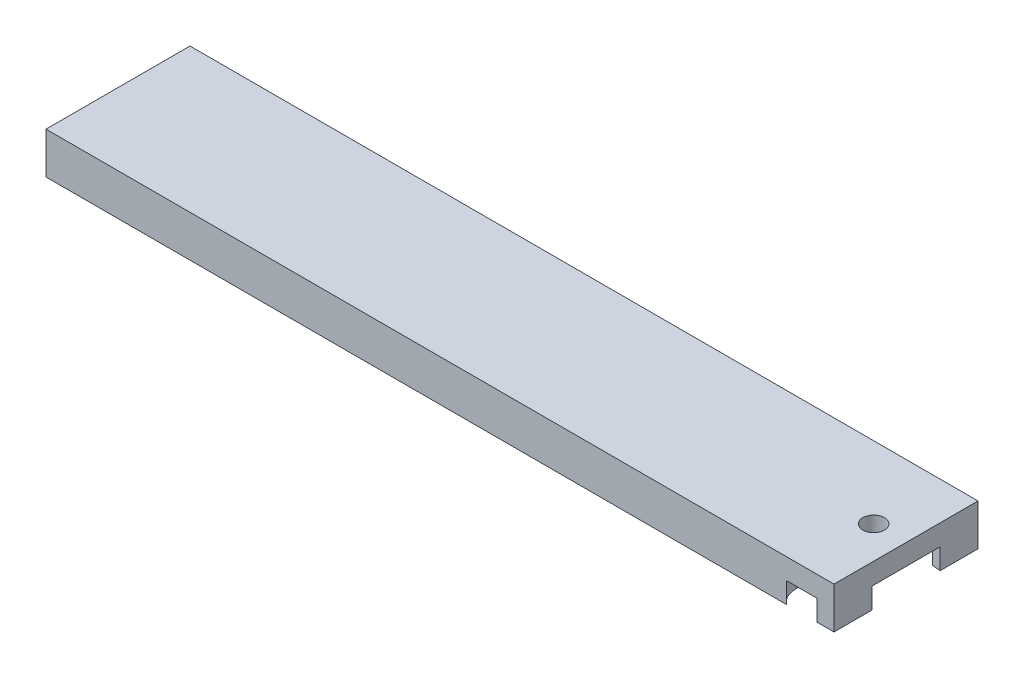
SolidWorks part; units mm, degrees
material "PVC Rígido"
ref_plane "Plano frontal" through (0, 0, 0) normal (0, 0, 1) x (1, 0, 0)
ref_plane "Plano superior" through (0, 0, 0) normal (0, 1, 0) x (1, 0, 0)
ref_plane "Plano direito" through (0, 0, 0) normal (1, 0, 0) x (0, 0, -1)
sketch "Esboço1" plane through (0, 0, 0) normal (0, 1, 0) x (1, 0, 0)
  line L0 (0, 0) -> (-14.05, 0) construction
  line L1 (-14.1591, 1.997) -> (-2.2091, 2.65)
  line L2 (-2.2091, -2.65) -> (-14.1591, -1.997)
  arc A0 (-2.2091, -2.65) -> (-2.2091, 2.65) centre (0, 0) ccw
  arc A1 (-14.1591, 1.997) -> (-14.1591, -1.997) centre (-14.05, 0) ccw
  dimension "D1" = 6.9
  dimension "D2" = 4
  dimension "D3" = 19.5
  dimension "D4" = 5.3
extrude "Ressalto-extrusão1" add sketch "Esboço1" against normal blind 1.4
sketch "Esboço2" plane through (0, -1.4, 0) normal (0, -1, 0) x (1, 0, 0)
  arc A0 (-2.2091, -2.65) -> (-2.2091, 2.65) centre (0, 0) ccw construction
  circle A1 centre (0, 0) radius 3.45
extrude "Ressalto-extrusão2" add sketch "Esboço2" along normal offset from surface (2.4 mm away) 3.8 up to face at (-7.242, 0, 0)
hole_wizard "Furo1" positions "Esboço9" profile "Esboço10" legacy end condition through all
sketch "Esboço9" plane through (0, 0, 0) normal (0, 1, 0) x (1, 0, 0)
  line L1 (-14.45, 0) -> (0, 0) construction
  arc A2 (-14.1591, 1.997) -> (-14.1591, -1.997) centre (-14.05, 0) ccw construction
  point P0 (-14.45, 0)
  point P19 (-16.05, 0)
  dimension "D1" = 1.6
sketch "Esboço10" plane through (-14.45, 0, 0) normal (1, 0, 0) x (0, 0, 1)
  line L0 (0, 0) -> (0, 3.8)
  line L1 (0, 3.8) -> (0.6, 3.8)
  line L2 (0.6, 3.8) -> (0.6, 0)
  line L3 (0.6, 0) -> (0, 0)
  line L4 (0, 110) -> (0, -10) construction
  dimension "Diameter" = 1.2
  dimension "Depth" = 3.8
pattern_linear "Padrão linear1" count 6 spacing 2 along (1, 0, 0) of "Furo1"
sketch "Esboço12" plane through (0, 0, 0) normal (0, 1, 0) x (1, 0, 0)
  line L0 (0.3041, 3.4366) -> (16.6263, 1.9922)
  line L1 (16.6263, -1.9922) -> (0.3041, -3.4366)
  arc A0 (-2.2091, -2.65) -> (-2.2091, 2.65) centre (0, 0) ccw construction
  arc A1 (0.3041, -3.4366) -> (0.3041, 3.4366) centre (0, 0) ccw
  arc A2 (16.6263, 1.9922) -> (16.6263, -1.9922) centre (16.45, 0) cw
  arc A3 (-14.1591, 1.997) -> (-14.1591, -1.997) centre (-14.05, 0) ccw construction
  dimension "D1" = 2
  dimension "D2" = 34.5
extrude "Ressalto-extrusão3" add sketch "Esboço12" against normal up to surface (1.4 mm away) up to face at (-12.45, -1.4, 0.6)
hole_wizard "Furo2" positions "Esboço13" profile "Esboço14" legacy end condition through all
sketch "Esboço13" plane through (0, 0, 0) normal (0, 1, 0) x (1, 0, 0)
  line L0 (0, 0) -> (16.85, 0) construction
  arc A0 (16.6263, -1.9922) -> (16.6263, 1.9922) centre (16.45, 0) ccw construction
  point P0 (16.85, 0)
  point P6 (18.45, 0)
  dimension "D1" = 1.6
sketch "Esboço14" plane through (16.85, 0, 0) normal (1, 0, 0) x (0, 0, 1)
  line L0 (0, 0) -> (0, 3.8)
  line L1 (0, 3.8) -> (0.6, 3.8)
  line L2 (0.6, 3.8) -> (0.6, 0)
  line L3 (0.6, 0) -> (0, 0)
  line L4 (0, 110) -> (0, -10) construction
  dimension "Diameter" = 1.2
  dimension "Depth" = 3.8
pattern_linear "Padrão linear2" count 7 spacing 2 along (-1, 0, 0) of "Furo2"
sketch "Esboço16" plane through (0, 0, 0) normal (0, 1, 0) x (1, 0, 0)
  line L0 (0, -6.45) -> (0, 6.45) construction
  line L1 (-1.9, -6.45) -> (-1.9, 6.45)
  line L2 (1.9, -6.45) -> (1.9, 6.45)
  arc A0 (-1.9, -6.45) -> (1.9, -6.45) centre (0, -6.45) ccw
  arc A1 (1.9, 6.45) -> (-1.9, 6.45) centre (0, 6.45) ccw
  point P2 (0, 0)
  dimension "D2" = 16.7
  dimension "D1" = 3.8
extrude "Ressalto-extrusão4" add sketch "Esboço16" against normal up to surface (1.4 mm away) up to face at (14.85, -1.4, 0.6)
hole_wizard "Furo3" positions "Esboço17" profile "Esboço18" legacy end condition through all
sketch "Esboço17" plane through (0, 0, 0) normal (0, 1, 0) x (1, 0, 0)
  point P0 (0, -6.45)
sketch "Esboço18" plane through (0, 0, 6.45) normal (1, 0, 0) x (0, 0, 1)
  line L0 (0, 0) -> (0, 3.8)
  line L1 (0, 3.8) -> (0.6, 3.8)
  line L2 (0.6, 3.8) -> (0.6, 0)
  line L3 (0.6, 0) -> (0, 0)
  line L4 (0, 110) -> (0, -10) construction
  dimension "Diameter" = 1.2
  dimension "Depth" = 3.8
pattern_linear "Padrão linear3" count 2 spacing 2 along (0, 0, -1) of "Furo3"
pattern_circular "PadrãoCircular1" count 2 over 360 about axis through (0, 0, 0) along (0, 1, 0) of "Padrão linear3", "Furo3"
hole_wizard "Furo4" positions "Esboço3" profile "Esboço4" legacy
sketch "Esboço3" plane through (0, -3.8, 0) normal (0, -1, 0) x (-1, 0, 0)
  point P0 (0, 0)
sketch "Esboço4" plane through (0, -3.8, 0) normal (1, 0, 0) x (0, 0, -1)
  line L0 (0, 0) -> (0, 2)
  line L1 (0, 2) -> (2.475, 2)
  line L2 (2.475, 2) -> (2.475, 0)
  line L3 (2.475, 0) -> (0, 0)
  line L4 (0, 110) -> (0, -10) construction
  dimension "Diameter" = 4.95
  dimension "Depth" = 2
hole_wizard "Furo5" positions "Esboço5" profile "Esboço6" legacy
sketch "Esboço5" plane through (0, 0, 0) normal (0, 1, 0) x (1, 0, 0)
  point P0 (0, 0)
sketch "Esboço6" plane through (0, 0, 0) normal (1, 0, 0) x (0, 0, 1)
  line L0 (0, 0) -> (0, 1)
  line L1 (0, 1) -> (2.3, 1)
  line L2 (2.3, 1) -> (2.3, 0)
  line L3 (2.3, 0) -> (0, 0)
  line L4 (0, 110) -> (0, -10) construction
  dimension "Diameter" = 4.6
  dimension "Depth" = 1
hole_wizard "Furo6" positions "Esboço7" profile "Esboço8" legacy end condition through all
sketch "Esboço7" plane through (0, 0, 0) normal (0, 1, 0) x (1, 0, 0)
  point P0 (0, 0)
sketch "Esboço8" plane through (0, 0, 0) normal (1, 0, 0) x (0, 0, 1)
  line L0 (0, 0) -> (0, 3.8)
  line L1 (0, 3.8) -> (1.05, 3.8)
  line L2 (1.05, 3.8) -> (1.05, 0)
  line L3 (1.05, 0) -> (0, 0)
  line L4 (0, 110) -> (0, -10) construction
  dimension "Diameter" = 2.1
  dimension "Depth" = 3.8
sketch "Esboço11" plane through (0, -3.8, 0) normal (0, -1, 0) x (1, 0, 0)
  line L0 (-0.0981, 2.4731) -> (0, 2.375)
  line L1 (0, 2.375) -> (0.0981, 2.4731)
  line L2 (0, 0) -> (0, 2.475) construction
  circle A0 centre (0, 0) radius 2.375 construction
  circle A1 centre (0, 0) radius 2.475
  arc A2 (0.0981, 2.4731) -> (-0.0981, 2.4731) centre (0, 0) ccw
  dimension "D3" = 4.75
  dimension "D2" = 0.1
  dimension "D1" = 0
extrude "Ressalto-extrusão5" add sketch "Esboço11" against normal up to surface (2 mm away) up to face at (0, -1.8, 1.05)
pattern_circular "PadrãoCircular2" count 60 over 360 about axis through (0, 0, 0) along (0, 1, 0) of "Ressalto-extrusão5"
sketch "Sketch1" plane through (0, 0, 0) normal (0, 1, 0) x (1, 0, 0)
  line L8 (-1.9, 6.45) -> (-1.9, 2.8797)
  line L9 (-2.2091, 2.65) -> (-14.1591, 1.997)
  line L10 (-14.1591, -1.997) -> (-2.2091, -2.65)
  line L11 (-1.9, -2.8797) -> (-1.9, -6.45)
  line L12 (1.9, -6.45) -> (1.9, -3.2953)
  line L13 (1.9, -3.2953) -> (16.6263, -1.9922)
  line L14 (16.6263, 1.9922) -> (1.9, 3.2953)
  line L15 (1.9, 3.2953) -> (1.9, 6.45)
  line L16 (-1.9, 6.45) -> (-1.9, 2.8797)
  line L17 (-2.2091, 2.65) -> (-14.1591, 1.997)
  line L18 (-14.1591, -1.997) -> (-2.2091, -2.65)
  line L19 (-1.9, -2.8797) -> (-1.9, -6.45)
  line L20 (1.9, -6.45) -> (1.9, -3.2953)
  line L21 (1.9, -3.2953) -> (16.6263, -1.9922)
  line L22 (16.6263, 1.9922) -> (1.9, 3.2953)
  line L23 (1.9, 3.2953) -> (1.9, 6.45)
  line L32 (8.9, 3.6798) -> (8.9, 8.6798)
  line L33 (8.9, 8.6798) -> (-91.1, 8.6798)
  line L34 (-91.1, 8.6798) -> (-91.1, -8.6798)
  line L35 (-91.1, -8.6798) -> (8.9, -8.6798)
  line L36 (8.9, -8.6798) -> (8.9, -3.6798)
  line L40 (-2.9, 6.45) -> (-2.9, 3.6137)
  line L41 (-2.9, 3.6137) -> (-14.2137, 2.9955)
  line L42 (-14.2137, -2.9955) -> (-2.9, -3.6137)
  line L43 (-2.9, -3.6137) -> (-2.9, -6.45)
  line L44 (2.9, -6.45) -> (2.9, -4.2108)
  line L45 (2.9, -4.2108) -> (16.7144, -2.9883)
  line L46 (16.7144, 2.9883) -> (2.9, 4.2108)
  line L47 (2.9, 4.2108) -> (2.9, 6.45)
  line L48 (-2.9, 6.45) -> (-2.9, 3.6137)
  line L49 (-2.9, 3.6137) -> (-14.2137, 2.9955)
  line L50 (-14.2137, -2.9955) -> (-2.9, -3.6137)
  line L51 (-2.9, -3.6137) -> (-2.9, -6.45)
  line L52 (2.9, -6.45) -> (2.9, -4.2108)
  line L53 (2.9, -4.2108) -> (16.7144, -2.9883)
  line L54 (16.7144, 2.9883) -> (2.9, 4.2108)
  line L55 (2.9, 4.2108) -> (2.9, 6.45)
  arc A8 (-1.9, 2.8797) -> (-2.2091, 2.65) centre (0, 0) ccw
  arc A9 (-14.1591, 1.997) -> (-14.1591, -1.997) centre (-14.05, 0) ccw
  arc A10 (-2.2091, -2.65) -> (-1.9, -2.8797) centre (0, 0) ccw
  arc A11 (-1.9, -6.45) -> (1.9, -6.45) centre (0, -6.45) ccw
  arc A12 (16.6263, -1.9922) -> (16.6263, 1.9922) centre (16.45, 0) ccw
  arc A13 (1.9, 6.45) -> (-1.9, 6.45) centre (0, 6.45) ccw
  arc A14 (-1.9, 2.8797) -> (-2.2091, 2.65) centre (0, 0) ccw
  arc A15 (-14.1591, 1.997) -> (-14.1591, -1.997) centre (-14.05, 0) ccw
  arc A16 (-2.2091, -2.65) -> (-1.9, -2.8797) centre (0, 0) ccw
  arc A17 (-1.9, -6.45) -> (1.9, -6.45) centre (0, -6.45) ccw
  arc A18 (16.6263, -1.9922) -> (16.6263, 1.9922) centre (16.45, 0) ccw
  arc A19 (1.9, 6.45) -> (-1.9, 6.45) centre (0, 6.45) ccw
  arc A30 (-14.2137, 2.9955) -> (-14.2137, -2.9955) centre (-14.05, 0) ccw
  arc A31 (-2.9, -6.45) -> (2.9, -6.45) centre (0, -6.45) ccw
  arc A32 (16.7144, -2.9883) -> (16.7144, 2.9883) centre (16.45, 0) ccw
  arc A33 (2.9, 6.45) -> (-2.9, 6.45) centre (0, 6.45) ccw
  arc A34 (-14.2137, 2.9955) -> (-14.2137, -2.9955) centre (-14.05, 0) ccw
  arc A35 (-2.9, -6.45) -> (2.9, -6.45) centre (0, -6.45) ccw
  arc A36 (16.7144, -2.9883) -> (16.7144, 2.9883) centre (16.45, 0) ccw
  arc A37 (2.9, 6.45) -> (-2.9, 6.45) centre (0, 6.45) ccw
  dimension "D1" = 0
  dimension "D3" = 5
  dimension "D4" = 5
  dimension "D5" = 6
  dimension "D6" = 100
  dimension "D2" = 1
extrude "Boss-Extrude1" add sketch "Sketch1" along normal blind 5 separate body contours A37 L33 L34 L35 A35 L51 L50 A34 L49 L48 | A37 L55 L54 L32 L33 | A35 L35 L36 L53 L52
sketch "Sketch2" plane through (0, 5, 0) normal (0, 1, 0) x (1, 0, 0)
  line L1 (-91.1, 8.6798) -> (8.9, 8.6798)
  line L2 (-91.1, 8.6798) -> (-91.1, -8.6798)
  line L3 (-91.1, -8.6798) -> (8.9, -8.6798)
  line L4 (8.9, 8.6798) -> (8.9, -8.6798)
extrude "Boss-Extrude2" add sketch "Sketch2" against normal blind 2.5
sketch "Sketch3" plane through (0, -1.8, 0) normal (0, -1, 0) x (1, 0, 0)
  circle A0 centre (0, 0) radius 1.3
  dimension "D1" = 2.6
extrude "Cut-Extrude1" cut sketch "Sketch3" against normal through all
sketch "Sketch4" plane through (0, 0, 0) normal (0, -1, 0) x (1, 0, 0)
  line L1 (-20.9627, 17.0491) -> (31.2088, 17.0491)
  line L2 (-20.9627, 17.0491) -> (-20.9627, -20.6638)
  line L3 (-20.9627, -20.6638) -> (31.2088, -20.6638)
  line L4 (31.2088, 17.0491) -> (31.2088, -20.6638)
extrude "Cut-Extrude2" cut sketch "Sketch4" along normal through all
sketch "Sketch5" plane through (0, 0, 0) normal (0, -1, 0) x (1, 0, 0)
  line L0 (-14.2137, 2.9955) -> (-21.7137, 2.5857)
  line L1 (-14.2137, -2.9955) -> (-21.7137, -2.5857)
  line L2 (-14.2137, 2.9955) -> (-2.9, 3.6137) construction
  line L3 (-2.9, -3.6137) -> (-14.2137, -2.9955) construction
  line L4 (-14.2137, 2.9955) -> (-14.2137, -2.9955)
  arc A0 (-21.7137, 2.5857) -> (-21.7137, -2.5857) centre (-21.7137, 0) ccw
  dimension "D1" = 180
  dimension "D2" = 180
  dimension "D3" = 7.5
  dimension "D4" = 7.5
extrude "Cut-Extrude3" cut sketch "Sketch5" against normal up to surface (2.5 mm away) up to face at (0, 2.5, 1.3)
sketch "Sketch6" plane through (0, 0, 0) normal (0, -1, 0) x (1, 0, 0)
  line L0 (8.9, -8.6798) -> (1.8542, -8.6798) construction
  line L1 (8.9, 8.6798) -> (3.9, 8.6798)
  line L2 (8.9, 8.6798) -> (8.9, -8.6798)
  line L3 (8.9, -8.6798) -> (3.9, -8.6798)
  line L4 (3.9, 8.6798) -> (3.9, -8.6798)
  dimension "D1" = 5
extrude "Cut-Extrude5" cut sketch "Sketch6" against normal blind 10
